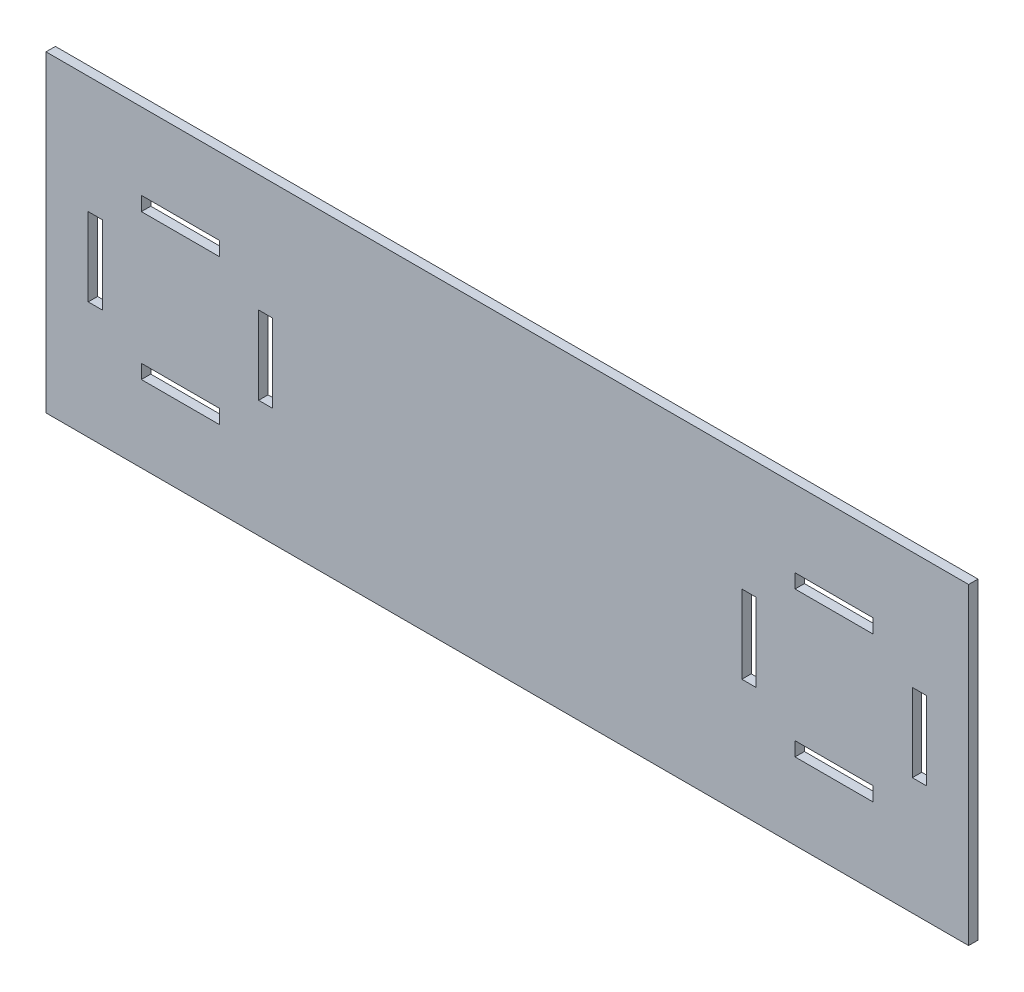
SolidWorks part; units mm, degrees
ref_plane "Plano frontal" through (0, 0, 0) normal (0, 0, 1) x (1, 0, 0)
ref_plane "Plano superior" through (0, 0, 0) normal (0, 1, 0) x (1, 0, 0)
ref_plane "Plano direito" through (0, 0, 0) normal (1, 0, 0) x (0, 0, -1)
sketch "Esboço1" plane through (0, 0, 0) normal (0, 0, 1) x (1, 0, 0)
  line L1 (-147.5, -50) -> (147.5, -50)
  line L2 (-147.5, -50) -> (-147.5, 50)
  line L3 (-147.5, 50) -> (147.5, 50)
  line L4 (147.5, -50) -> (147.5, 50)
  line L5 (-147.5, -50) -> (147.5, 50) construction
  line L6 (-147.5, 50) -> (147.5, -50) construction
  point P0 (0, 0)
  dimension "D1" = 295
  dimension "D2" = 100
extrude "Ressalto-extrusão1" add sketch "Esboço1" along normal blind 3
sketch "Esboço2" plane through (0, 0, 3) normal (0, 0, 1) x (1, 0, 0)
  line L0 (-147.5, 0) -> (147.5, 0) construction
  line L1 (-147.5, 50) -> (-147.5, -50) construction
  line L2 (147.5, -50) -> (147.5, 50) construction
  line L3 (0, 50) -> (0, -50) construction
  line L4 (147.5, 50) -> (-147.5, 50) construction
  line L5 (-147.5, -50) -> (147.5, -50) construction
  line L6 (-104.5, 50) -> (-104.5, -50) construction
  line L11 (134, 12.5) -> (129.5, 12.5)
  line L12 (129.5, -12.5) -> (129.5, 12.5)
  line L13 (-79.5, -12.5) -> (-75, -12.5)
  line L14 (-79.5, -12.5) -> (-79.5, 12.5)
  line L15 (-79.5, 12.5) -> (-75, 12.5)
  line L16 (-75, -12.5) -> (-75, 12.5)
  line L17 (-79.5, -12.5) -> (-75, 12.5) construction
  line L18 (-79.5, 12.5) -> (-75, -12.5) construction
  line L19 (-134, -12.5) -> (-129.5, -12.5)
  line L20 (-134, -12.5) -> (-134, 12.5)
  line L21 (-134, 12.5) -> (-129.5, 12.5)
  line L22 (-129.5, -12.5) -> (-129.5, 12.5)
  line L23 (-134, -12.5) -> (-129.5, 12.5) construction
  line L24 (-134, 12.5) -> (-129.5, -12.5) construction
  line L25 (-117, 21) -> (-92, 21)
  line L26 (-117, -25.5) -> (-92, -25.5)
  line L27 (-117, -25.5) -> (-117, -21)
  line L28 (-117, -21) -> (-92, -21)
  line L29 (-92, -25.5) -> (-92, -21)
  line L30 (-117, -25.5) -> (-92, -21) construction
  line L31 (-117, -21) -> (-92, -25.5) construction
  line L32 (-92, 25.5) -> (-92, 21)
  line L33 (-117, 25.5) -> (-92, 25.5)
  line L34 (-117, 25.5) -> (-117, 21)
  line L35 (134, -12.5) -> (129.5, -12.5)
  line L36 (134, -12.5) -> (134, 12.5)
  line L37 (79.5, 12.5) -> (75, 12.5)
  line L38 (75, -12.5) -> (75, 12.5)
  line L39 (79.5, -12.5) -> (75, -12.5)
  line L40 (79.5, -12.5) -> (79.5, 12.5)
  line L41 (117, -21) -> (92, -21)
  line L42 (92, -25.5) -> (92, -21)
  line L43 (117, -25.5) -> (92, -25.5)
  line L44 (117, -25.5) -> (117, -21)
  line L45 (117, 25.5) -> (117, 21)
  line L46 (117, 25.5) -> (92, 25.5)
  line L47 (92, 25.5) -> (92, 21)
  line L48 (117, 21) -> (92, 21)
  point P13 (-104.5, 0)
  point P17 (-77.25, 0)
  point P22 (-131.75, 0)
  point P29 (-104.5, -23.25)
  dimension "D3" = 4.5
  dimension "D4" = 25
  dimension "D6" = 68
  dimension "D9" = 50
  dimension "D10" = 25
  dimension "D11" = 4.5
  dimension "D12" = 42
  dimension "D13" = 25
extrude "Corte-extrusão1" cut sketch "Esboço2" against normal through all
